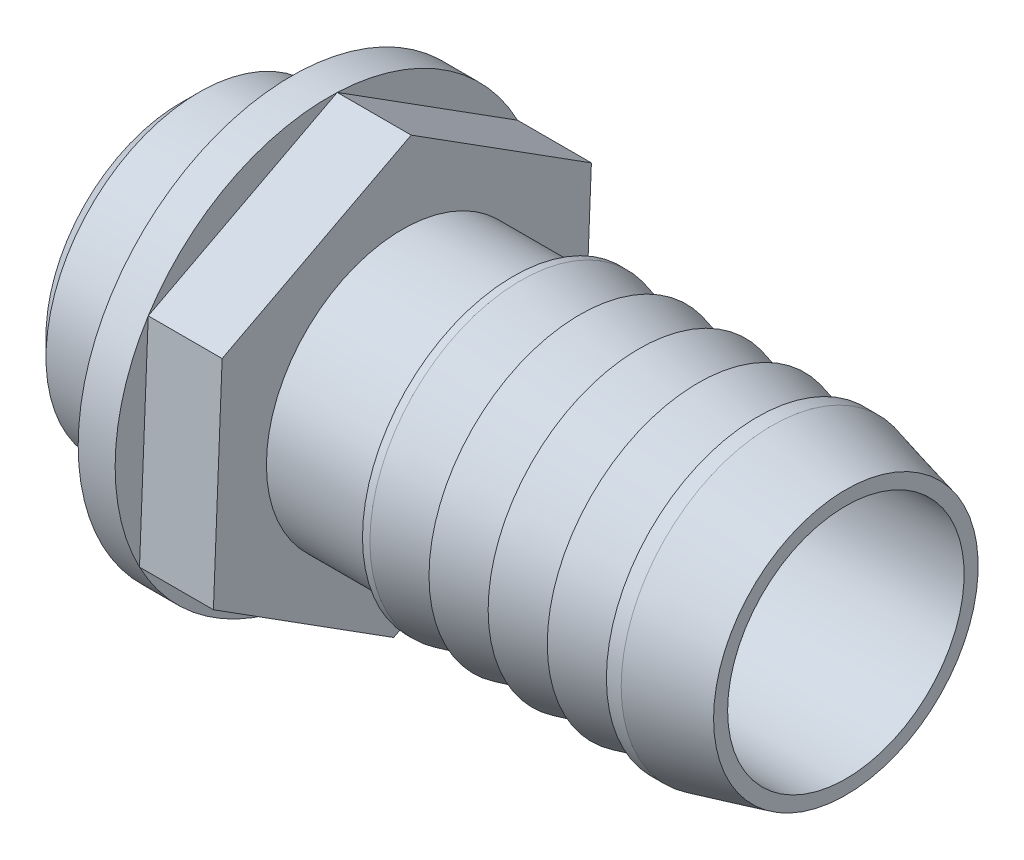
SolidWorks part; units mm, degrees
ref_plane "Plan de face" through (0, 0, 0) normal (0, 0, 1) x (1, 0, 0)
ref_plane "Plan de dessus" through (0, 0, 0) normal (0, 1, 0) x (1, 0, 0)
ref_plane "Plan de droite" through (0, 0, 0) normal (1, 0, 0) x (0, 0, -1)
ref_plane "Plan1"
sketch "Esquisse1" plane through (0, 0, 0) normal (0, 0, 1) x (1, 0, 0)
  line L0 (0, 5.08) -> (19.05, 5.08)
  line L1 (19.05, 5.08) -> (19.05, 6.477)
  line L2 (19.05, 6.477) -> (15.24, 6.477)
  line L3 (15.24, 6.477) -> (15.24, 5.842)
  line L4 (15.24, 5.842) -> (12.7, 6.477)
  line L5 (12.7, 6.477) -> (12.7, 5.842)
  line L6 (12.7, 5.842) -> (10.16, 6.477)
  line L7 (10.16, 6.477) -> (10.16, 5.842)
  line L8 (10.16, 5.842) -> (7.62, 6.477)
  line L9 (7.62, 6.477) -> (7.62, 5.842)
  line L10 (7.62, 5.842) -> (5.08, 6.477)
  line L11 (5.08, 6.477) -> (4.7625, 6.477)
  line L12 (4.7625, 6.477) -> (4.7625, 5.842)
  line L13 (4.7625, 5.842) -> (0, 5.842)
  line L14 (0, 5.842) -> (0, 5.08)
  line L15 (0, 0) -> (142.9139, 0) construction
  dimension "D1" = 5.08
  dimension "D2" = 19.05
  dimension "D3" = 3.81
  dimension "D4" = 2.54
  dimension "D5" = 2.54
  dimension "D6" = 2.54
  dimension "D7" = 2.54
  dimension "D8" = 165.964
  dimension "D9" = 19.05
  dimension "D10" = 19.05
  dimension "D11" = 4.7625
revolve "Revolution1" add sketch "Esquisse1" angle 360 about L15
chamfer "Chamfer1" distance 0.7938 distance2 3.175 1 edges at (19.05, 0, 6.477)
ref_plane "Plan2"
sketch "Esquisse2" plane through (0, 0, 0) normal (-1, 0, 0) x (0, 0, 1)
  line L0 (0.3759, -9.1577) -> (-7.7429, -4.9044)
  line L1 (-7.7429, -4.9044) -> (-8.1188, 4.2533)
  line L2 (-8.1188, 4.2533) -> (-0.3759, 9.1577)
  line L3 (-0.3759, 9.1577) -> (7.7429, 4.9044)
  line L4 (7.7429, 4.9044) -> (8.1188, -4.2533)
  line L5 (8.1188, -4.2533) -> (0.3759, -9.1577)
  dimension "D1" = 15.875
extrude "Extrusion1" add sketch "Esquisse2" along normal blind 3.175
sketch "Esquisse3" plane through (-3.175, 0, 0) normal (-1, 0, 0) x (0, 0, 1)
  circle A0 centre (0, 0) radius 9.1654
extrude "Extrusion2" add sketch "Esquisse3" along normal blind 1.5875
sketch "Esquisse4" plane through (-4.7625, 0, 0) normal (-1, 0, 0) x (0, 0, 1)
  circle A0 centre (0, 0) radius 6.5786
  dimension "D1" = 13.1572
extrude "Thread1" add sketch "Esquisse4" along normal blind 4.7625
cosmetic thread "Représentation de filetage1" parameters "D2"=0
chamfer "Chamfer2" distance 0.7938 distance2 0.7938 1 edges at (-9.525, 0, 6.5786)
hole_wizard "Hole1" positions "Esquisse6" profile "Esquisse5" legacy end condition through all
sketch "Esquisse6" plane through (-9.525, 0, 0) normal (-1, 0, 0) x (0, 0, 1)
  point P1 (0, 0)
sketch "Esquisse5" plane through (-9.525, 0, 0) normal (0, 1, 0) x (0, 0, 1)
  line L0 (0, 0) -> (0, 28.575)
  line L1 (0, 28.575) -> (5.08, 28.575)
  line L2 (5.08, 28.575) -> (5.08, 0)
  line L3 (5.08, 0) -> (0, 0)
  line L4 (0, 110) -> (0, -10) construction
  dimension "Diamètre" = 10.16
  dimension "Profondeur" = 28.575
